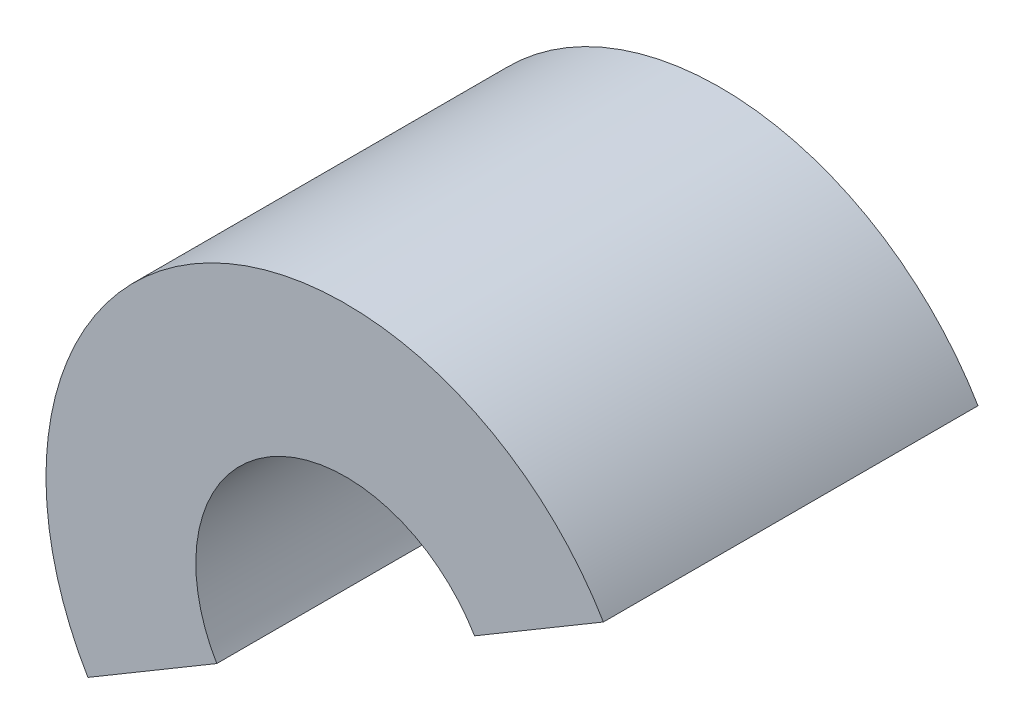
SolidWorks part; units mm, degrees
ref_plane "Front Plane" through (0, 0, 0) normal (0, 0, 1) x (1, 0, 0)
ref_plane "Top Plane" through (0, 0, 0) normal (0, 1, 0) x (1, 0, 0)
ref_plane "Right Plane" through (0, 0, 0) normal (1, 0, 0) x (0, 0, -1)
sketch "Sketch1" plane through (0, 0, 0) normal (0, 0, 1) x (1, 0, 0)
  line L0 (-17.2021, -10.2023) -> (17.2021, 10.2023)
  arc A0 (17.2021, 10.2023) -> (-17.2021, -10.2023) centre (0, 0) ccw
  arc A1 (-8.6011, -5.1011) -> (8.6011, 5.1011) centre (0, 0) cw
  dimension "D2" = 10
  dimension "D1" = 40
extrude "Boss-Extrude1" add sketch "Sketch1" along normal blind 25 contours L0 A1 A0
